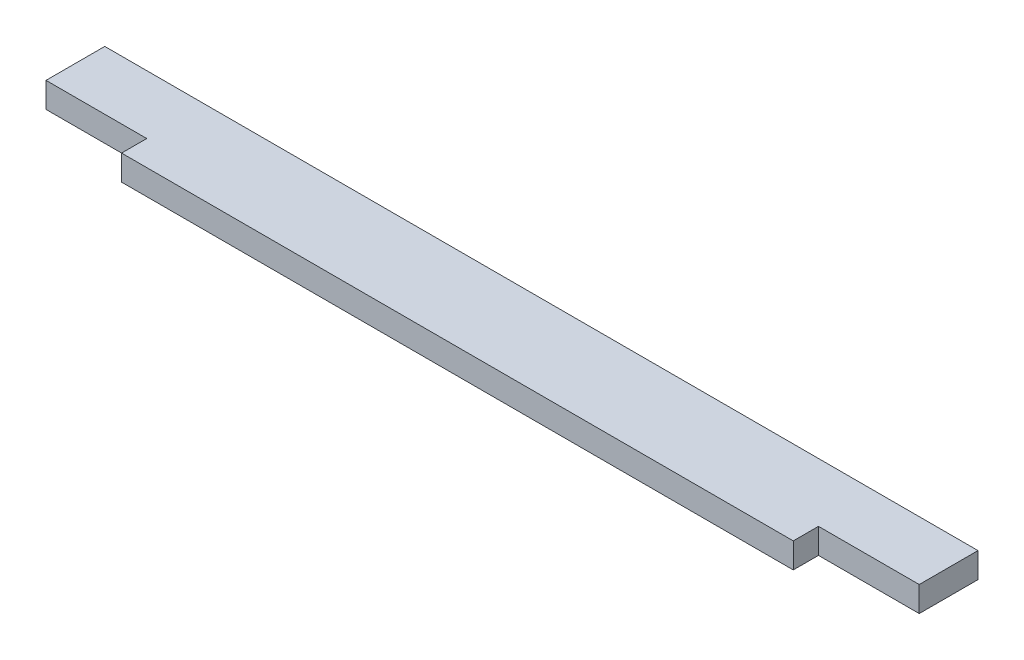
SolidWorks part; units mm, degrees
ref_plane "Front" through (0, 0, 0) normal (0, 0, 1) x (1, 0, 0)
ref_plane "Top" through (0, 0, 0) normal (0, 1, 0) x (1, 0, 0)
ref_plane "Right" through (0, 0, 0) normal (1, 0, 0) x (0, 0, -1)
sketch "Sketch1" plane through (0, 0, 0) normal (0, 1, 0) x (1, 0, 0)
  line L1 (-52, 5) -> (52, 5)
  line L2 (-52, 5) -> (-52, -5)
  line L3 (-52, -5) -> (52, -5)
  line L4 (52, 5) -> (52, -5)
  line L5 (-52, 5) -> (52, -5) construction
  line L6 (-52, -5) -> (52, 5) construction
  point P0 (0, 0)
  dimension "D1" = 104
  dimension "D2" = 10
extrude "Boss-Extrude1" add sketch "Sketch1" along normal blind 3
sketch "Sketch2" plane through (0, 3, 0) normal (0, 1, 0) x (1, 0, 0)
  line L0 (-40, -5) -> (-52, -5)
  line L1 (-52, -5) -> (52, -5) construction
  line L2 (0, -5) -> (-40, -5)
  line L3 (0, -5) -> (40, -5)
  line L4 (40, -5) -> (40, -2)
  line L5 (40, -2) -> (-40, 0)
  line L6 (-40, 0) -> (-40, -5)
  line L7 (-40, 0) -> (-52, 0)
  line L8 (-52, 5) -> (-52, -5) construction
  line L9 (-52, 0) -> (-52, -5)
  line L10 (-40, -5) -> (-40, 0)
  line L11 (52, -5) -> (40, -5)
  line L12 (40, -2) -> (52, -2)
  line L13 (-40, -5) -> (-40, -2)
  line L14 (-40, -2) -> (-52, -2)
  line L15 (52, -2) -> (52, -5)
  line L16 (-52, -2) -> (-52, -5)
  line M4 (52, -5) -> (52, 5)
  line M6 (-52, 5) -> (-52, -5)
  line M7 (-52, -5) -> (52, -5)
  dimension "D1" = 40
  dimension "D2" = 40
  dimension "D3" = 3
extrude "Cut-Extrude2" cut sketch "Sketch2" against normal through all contours L12 L4 M7 M4 | L6 L7 M6 M7
